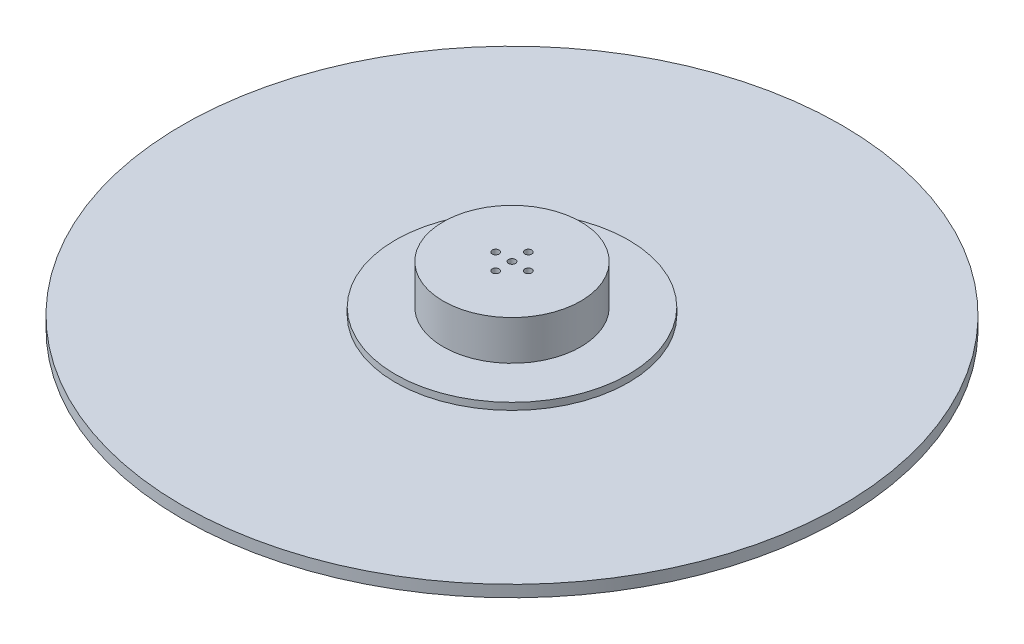
SolidWorks part; units mm, degrees
ref_plane "前视基准面" through (0, 0, 0) normal (0, 0, 1) x (1, 0, 0)
ref_plane "上视基准面" through (0, 0, 0) normal (0, 1, 0) x (1, 0, 0)
ref_plane "右视基准面" through (0, 0, 0) normal (1, 0, 0) x (0, 0, -1)
other "Configuration Table"
sketch "草图1" plane through (0, 0, 0) normal (0, 1, 0) x (1, 0, 0)
  circle A0 centre (0, 0) radius 141.4
  dimension "D1" = 282.8
extrude "凸台-拉伸1" add sketch "草图1" along normal blind 5
sketch "草图2" plane through (0, 5, 0) normal (0, 1, 0) x (1, 0, 0)
  circle A0 centre (0, 0) radius 50
extrude "凸台-拉伸2" add sketch "草图2" along normal blind 3
sketch "草图3" plane through (0, 8, 0) normal (0, 1, 0) x (1, 0, 0)
  circle A0 centre (0, 0) radius 29.5
  dimension "D1" = 59
extrude "凸台-拉伸3" add sketch "草图3" along normal blind 17
sketch "草图4" plane through (0, 0, 0) normal (0, -1, 0) x (1, 0, 0)
  circle A0 centre (0, 0) radius 27
  dimension "D1" = 54
extrude "切除-拉伸1" cut sketch "草图4" against normal blind 22
sketch "草图5" plane through (0, 22, 0) normal (0, -1, 0) x (1, 0, 0)
  line L0 (0, 0) -> (0, 7) construction
  circle A0 centre (0, 0) radius 1.5
  circle A1 centre (0, 7) radius 1.5
  circle A2 centre (7, 0) radius 1.5
  circle A3 centre (0, -7) radius 1.5
  circle A4 centre (-7, 0) radius 1.5
  point P14 (0, 0)
  dimension "D1" = 4
extrude "切除-拉伸2" cut sketch "草图5" against normal through all
